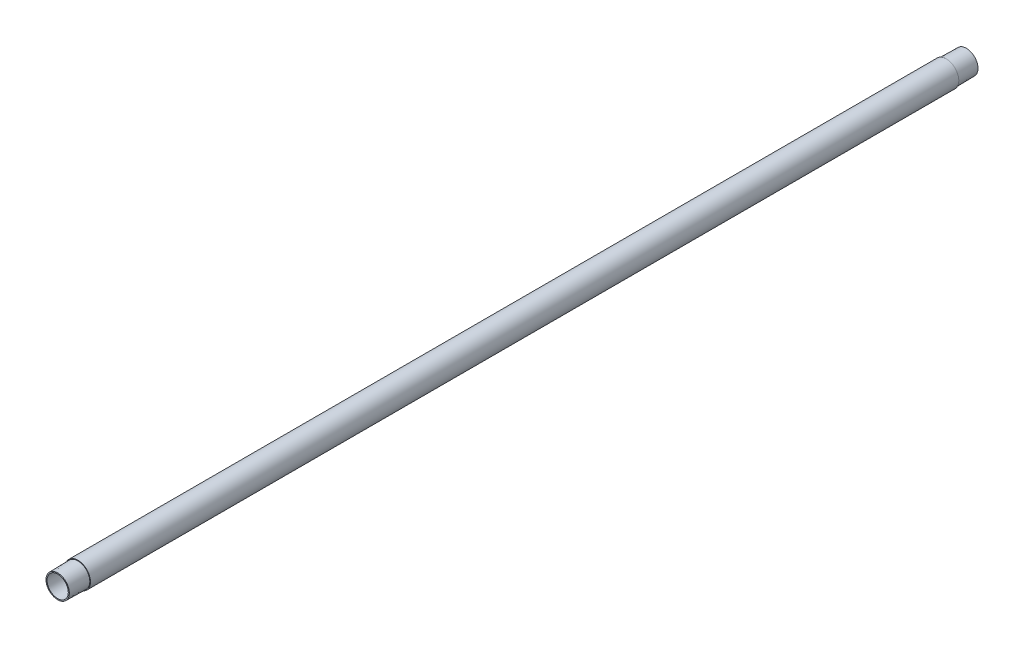
SolidWorks part; units mm, degrees
material "Plain Carbon Steel"
ref_plane "Front Plane" through (0, 0, 0) normal (0, 0, 1) x (1, 0, 0)
ref_plane "Top Plane" through (0, 0, 0) normal (0, 1, 0) x (1, 0, 0)
ref_plane "Right Plane" through (0, 0, 0) normal (1, 0, 0) x (0, 0, -1)
sketch "Sketch2" plane through (0, 0, 0) normal (0, 0, 1) x (1, 0, 0)
  circle A0 centre (0, 0) radius 6.35
  circle A1 centre (0, 0) radius 5.334
  dimension "D1" = 12.7
  dimension "D2" = 10.668
extrude "Boss-Extrude1" add sketch "Sketch2" along normal blind 457.2
sketch "Sketch3" plane through (0, 0, 0) normal (1, 0, 0) x (0, 0, -1)
  line L0 (-457.2, 8.9543) -> (-457.2, 5.8696)
  line L1 (-457.2, 5.8696) -> (-447.0506, 6.0202)
  line L2 (-447.0506, 6.0202) -> (-447.0506, 8.9543)
  line L3 (-447.0506, 8.9543) -> (-457.2, 8.9543)
  line L4 (-228.6, 0) -> (-228.6, 20.2099) construction
  line L5 (0, 0) -> (-457.2, 0) construction
  line L6 (-10.1494, 8.9543) -> (0, 8.9543)
  line L7 (-10.1494, 6.0202) -> (-10.1494, 8.9543)
  line L8 (0, 5.8696) -> (-10.1494, 6.0202)
  line L9 (0, 8.9543) -> (0, 5.8696)
revolve "Cut-Revolve3" cut sketch "Sketch3" angle 360 about L5
